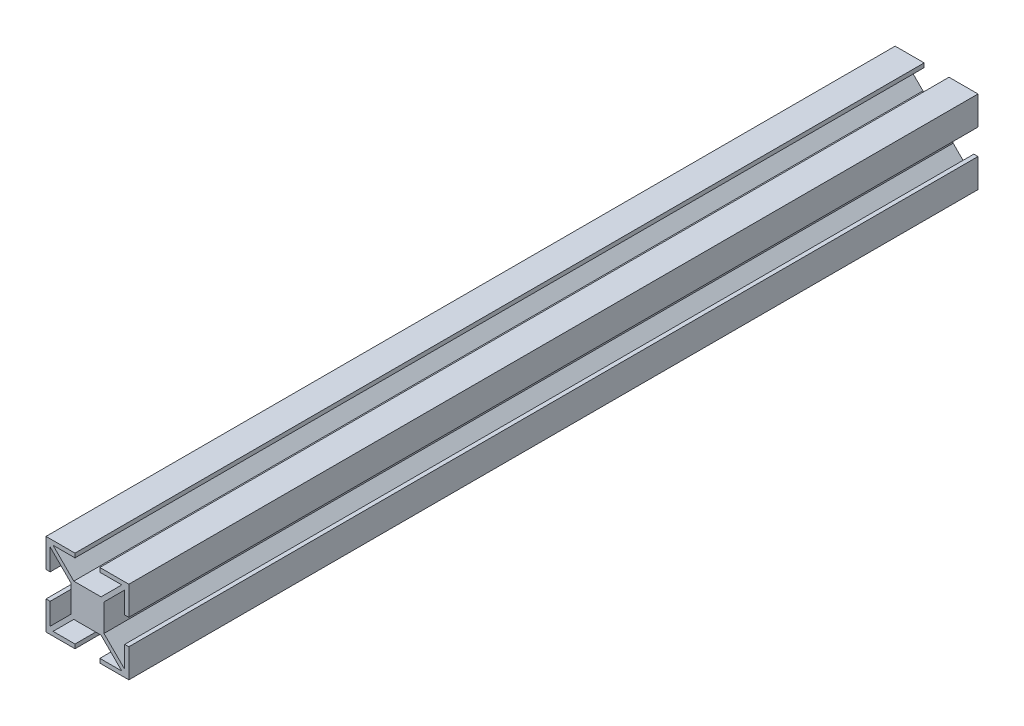
SolidWorks part; units mm, degrees
ref_plane "Front Plane" through (0, 0, 0) normal (0, 0, 1) x (1, 0, 0)
ref_plane "Top Plane" through (0, 0, 0) normal (0, 1, 0) x (1, 0, 0)
ref_plane "Right Plane" through (0, 0, 0) normal (1, 0, 0) x (0, 0, -1)
sketch "Sketch2" plane through (0, 0, 0) normal (0, 0, 1) x (1, 0, 0)
  line L0 (-10, 10) -> (-3, 10)
  line L1 (-3.2929, -4) -> (3.2929, -4)
  line L2 (-4, -3.2929) -> (-4, 3.2929)
  line L3 (-3.2929, 4) -> (3.2929, 4)
  line L4 (4, -3.2929) -> (4, 3.2929)
  line L5 (-4, -4) -> (4, 4) construction
  line L6 (-4, 4) -> (4, -4) construction
  line L7 (-10, -10) -> (10, -10) construction
  line L8 (-10, -10) -> (-10, 10) construction
  line L9 (-10, 10) -> (10, 10) construction
  line L10 (10, -10) -> (10, 10) construction
  line L11 (-10, -10) -> (10, 10) construction
  line L12 (-10, 10) -> (10, -10) construction
  line L13 (-10, 10) -> (-10, 3.074)
  line L14 (0, -11) -> (0, 11) construction
  line L15 (10, 10) -> (10, 3.074)
  line L16 (10, 10) -> (3, 10)
  line L17 (11, 0) -> (-11, 0) construction
  line L18 (10, -10) -> (10, -3.074)
  line L19 (10, -10) -> (3, -10)
  line L20 (-10, -10) -> (-3, -10)
  line L21 (-10, -10) -> (-10, -3.074)
  line L22 (-9, 8.2929) -> (-9, 3.074)
  line L23 (-8.2929, 9) -> (-3, 9)
  line L24 (-3, 10) -> (-3, 9)
  line L25 (-10, 3.074) -> (-9, 3.074)
  line L26 (-3, -10) -> (-3, -9)
  line L27 (-8.2929, -9) -> (-3, -9)
  line L28 (-9, -8.2929) -> (-9, -3.074)
  line L29 (-10, -3.074) -> (-9, -3.074)
  line L30 (10, 3.074) -> (9, 3.074)
  line L31 (9, 8.2929) -> (9, 3.074)
  line L32 (8.2929, 9) -> (3, 9)
  line L33 (3, 10) -> (3, 9)
  line L34 (3, -10) -> (3, -9)
  line L35 (8.2929, -9) -> (3, -9)
  line L36 (9, -8.2929) -> (9, -3.074)
  line L37 (10, -3.074) -> (9, -3.074)
  line L38 (-9, 9) -> (-3, 3) construction
  line L39 (-9, 8.2929) -> (-4, 3.2929)
  line L40 (-8.2929, 9) -> (-3.2929, 4)
  line L41 (-8.6464, 9.3536) -> (-2.6464, 3.3536) construction
  line L42 (-9.3536, 8.6464) -> (-3.3536, 2.6464) construction
  line L43 (-9, 9) -> (-3, 9) construction
  line L44 (-9, 9) -> (-9, 3.074) construction
  line L45 (9, 8.2929) -> (4, 3.2929)
  line L46 (8.2929, 9) -> (3.2929, 4)
  line L47 (9, -8.2929) -> (4, -3.2929)
  line L48 (8.2929, -9) -> (3.2929, -4)
  line L49 (-9, -8.2929) -> (-4, -3.2929)
  line L50 (-8.2929, -9) -> (-3.2929, -4)
  point P0 (0, 0)
  point P6 (0, 0)
  point P26 (-9, 5.6835)
  point P28 (-9, -5.6835)
  dimension "D1" = 8
  dimension "D2" = 8
  dimension "D3" = 20
  dimension "D4" = 20
  dimension "D5" = 1
  dimension "D8" = 45
  dimension "D9" = 6.5858
  dimension "D10" = 6.5858
  dimension "D11" = 1
  dimension "D6" = 0.5
  dimension "D7" = 0.5
extrude "Boss-Extrude1" add sketch "Sketch2" along normal blind 205
